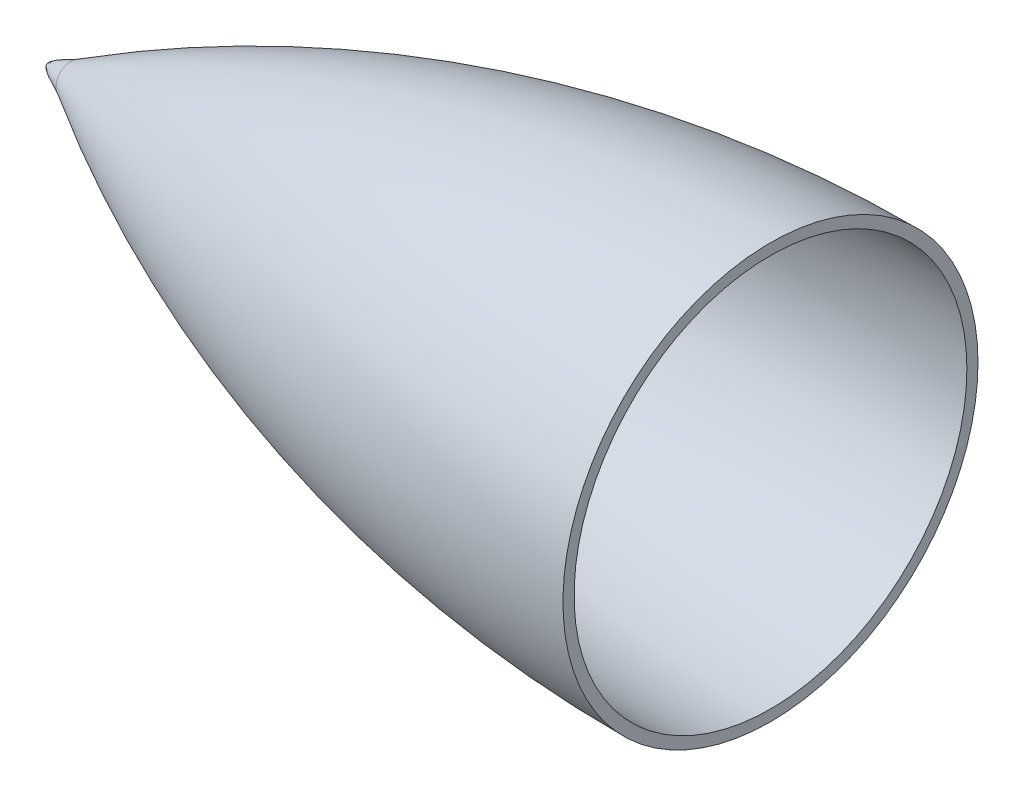
SolidWorks part; units mm, degrees
ref_plane "Front Plane" through (0, 0, 0) normal (0, 0, 1) x (1, 0, 0)
ref_plane "Top Plane" through (0, 0, 0) normal (0, 1, 0) x (1, 0, 0)
ref_plane "Right Plane" through (0, 0, 0) normal (1, 0, 0) x (0, 0, -1)
sketch "Sketch1" plane through (0, 0, 0) normal (0, 0, 1) x (1, 0, 0)
  line L0 (0, 0) -> (0, 240.1279) construction
  line L1 (-150, 240.1279) -> (-140.3343, 240.1279)
  line L2 (0, 280.8279) -> (0, 283.1279)
  line L6 (0, 280.8279) -> (0, 283.1279) construction
  line L13 (-131.4056, 245.1279) -> (0, 245.1279) construction
  line L14 (0, 245.1279) -> (81, 245.1279) construction
  line L15 (-150, 240.1279) -> (0, 240.1279) construction
  line L16 (0, 240.1279) -> (86, 240.1279) construction
  line L17 (-150, 240.1279) -> (-175.3476, 240.1279) construction
  line L18 (-140.3343, 240.1279) -> (-75, 240.1279) construction
  line L19 (-75, 267.8248) -> (-75, 270.6276)
  line L20 (0, 278.1279) -> (0, 283.1279) construction
  line L21 (81, 273.1279) -> (-5, 273.1279) construction
  line L22 (-5, 273.1279) -> (-5, 278.083) construction
  line L23 (86, 278.1279) -> (0, 278.1279) construction
  line L24 (86, 240.1279) -> (86, 278.1279) construction
  line L25 (81, 245.1279) -> (81, 273.1279) construction
  arc A0 (0, 283.1279) -> (-150, 240.1279) centre (0, 0) ccw
  arc A1 (-75, 267.8248) -> (-131.4056, 245.1279) centre (0, 0) ccw
  arc A3 (-75, 267.8248) -> (-140.3343, 240.1279) centre (0, 0) ccw
  arc A5 (-75, 267.8248) -> (-140.3343, 240.1279) centre (0, 0) ccw
  arc A6 (0, 280.8279) -> (-75, 270.6276) centre (0, 0) ccw
  arc A7 (0, 280.8279) -> (-148.7815, 238.1772) centre (0, 0) ccw construction
  arc A8 (-5, 278.083) -> (-131.4056, 245.1279) centre (0, 0) ccw construction
  arc A9 (-75, 267.8248) -> (-140.3343, 240.1279) centre (0, 0) ccw
  dimension "D1" = 150
  dimension "D2" = 43
  dimension "D4" = 5
  dimension "D6" = 2.3
  dimension "D7" = 75
revolve "Revolve1" add sketch "Sketch1" angle 360 about L17
sketch "Sketch2" plane through (0, 0, 0) normal (0, 0, 1) x (1, 0, 0)
  line L0 (-150, 240.1279) -> (-145, 240.1279)
  line L1 (-145, 240.1279) -> (-145, 243.1798)
  arc A1 (0, 283.1279) -> (-150, 240.1279) centre (0, 0) ccw construction
  arc A3 (-145, 243.1798) -> (-150, 240.1279) centre (0, 0) ccw
  dimension "D1" = 5
revolve "Cut-Revolve1" cut sketch "Sketch2" angle 360 about L0
sketch "Sketch4" plane through (0, 0, 0) normal (0, 0, 1) x (1, 0, 0)
  line L0 (-145, 240.1279) -> (-150, 240.1279)
  line L1 (-145, 243.1798) -> (-145, 237.076) construction
  line L2 (-145, 243.1798) -> (-145, 240.1279)
  spline S0 degree 3 poles (-150, 240.1279) (-149.5716, 241.0951) (-147.4765, 242.0623) (-145, 243.1798) knots 0.5 0.5 0.5 0.5 1 1 1 1
  dimension "D1" = 5
revolve "Revolve2" add sketch "Sketch4" angle 360 about L0
